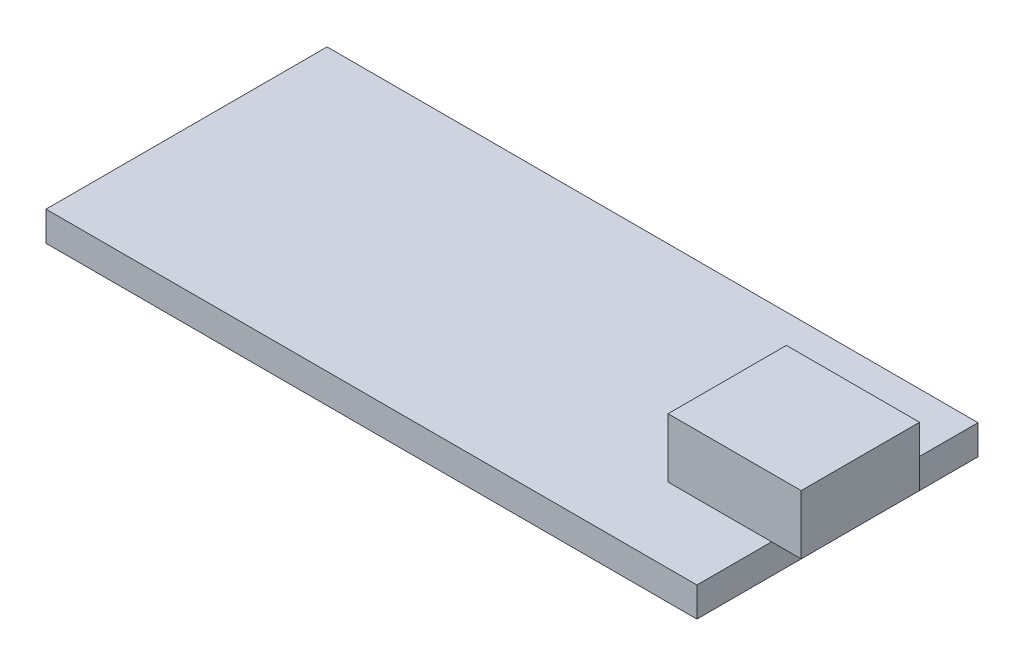
SolidWorks part; units mm, degrees
ref_plane "Front Plane" through (0, 0, 0) normal (0, 0, 1) x (1, 0, 0)
ref_plane "Top Plane" through (0, 0, 0) normal (0, 1, 0) x (1, 0, 0)
ref_plane "Right Plane" through (0, 0, 0) normal (1, 0, 0) x (0, 0, -1)
other "Configuration Table"
sketch "草图1" plane through (0, 0, 0) normal (0, 1, 0) x (1, 0, 0)
  line L1 (-22, -9.5) -> (22, -9.5)
  line L2 (-22, -9.5) -> (-22, 9.5)
  line L3 (-22, 9.5) -> (22, 9.5)
  line L4 (22, -9.5) -> (22, 9.5)
  line L5 (-22, -9.5) -> (22, 9.5) construction
  line L6 (-22, 9.5) -> (22, -9.5) construction
  point P0 (0, 0)
  dimension "D1" = 19
  dimension "D2" = 44
extrude "凸台-拉伸1" add sketch "草图1" along normal blind 2
sketch "草图2" plane through (0, 2, 0) normal (0, 1, 0) x (1, 0, 0)
  line L1 (24, -4.4512) -> (15, -4.4512)
  line L2 (24, -4.4512) -> (24, 3.5488)
  line L3 (24, 3.5488) -> (15, 3.5488)
  line L4 (15, -4.4512) -> (15, 3.5488)
  line L5 (24, -4.4512) -> (15, 3.5488) construction
  line L6 (24, 3.5488) -> (15, -4.4512) construction
  line L7 (22, -9.5) -> (22, 9.5) construction
  point P0 (19.5, -0.4512)
  point P5 (18.6021, 0)
  point P6 (18.151, 0)
  dimension "D1" = 8
  dimension "D2" = 9
  dimension "D3" = 2
extrude "凸台-拉伸2" add sketch "草图2" along normal blind 4
